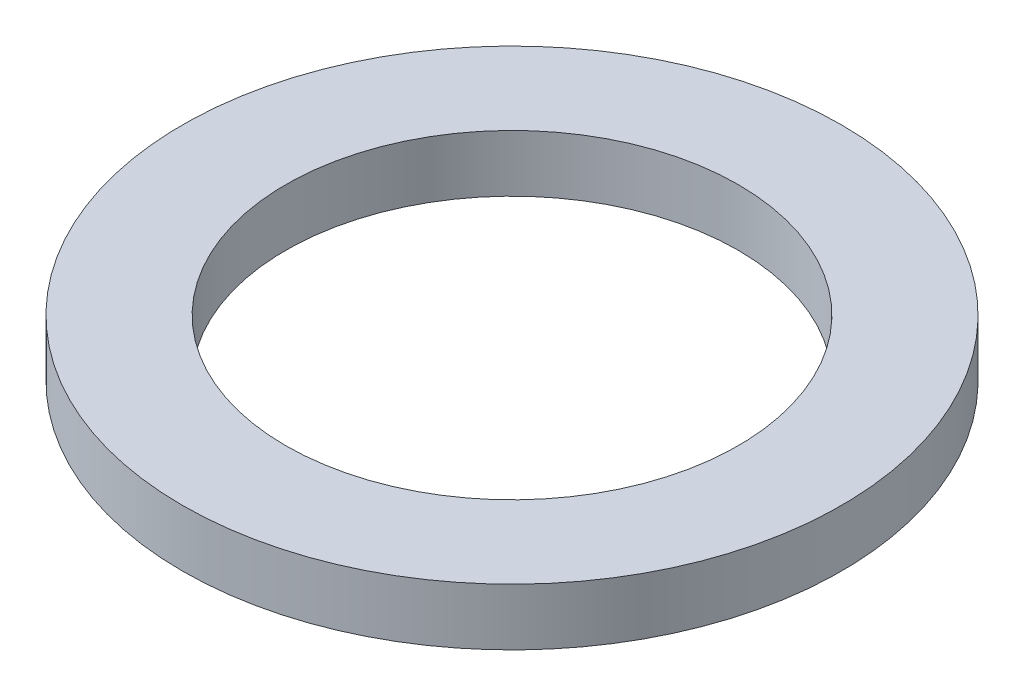
SolidWorks part; units mm, degrees
material "Nylon 6/10"
ref_plane "Front Plane" through (0, 0, 0) normal (0, 0, 1) x (1, 0, 0)
ref_plane "Top Plane" through (0, 0, 0) normal (0, 1, 0) x (1, 0, 0)
ref_plane "Right Plane" through (0, 0, 0) normal (1, 0, 0) x (0, 0, -1)
sketch "Sketch1" plane through (0, 0, 0) normal (0, 1, 0) x (1, 0, 0)
  circle A0 centre (0, 0) radius 1.9177
  circle A1 centre (0, 0) radius 2.794
  dimension "D1" = 3.8354
  dimension "D2" = 5.588
extrude "Boss-Extrude1" add sketch "Sketch1" along normal blind 0.4826
